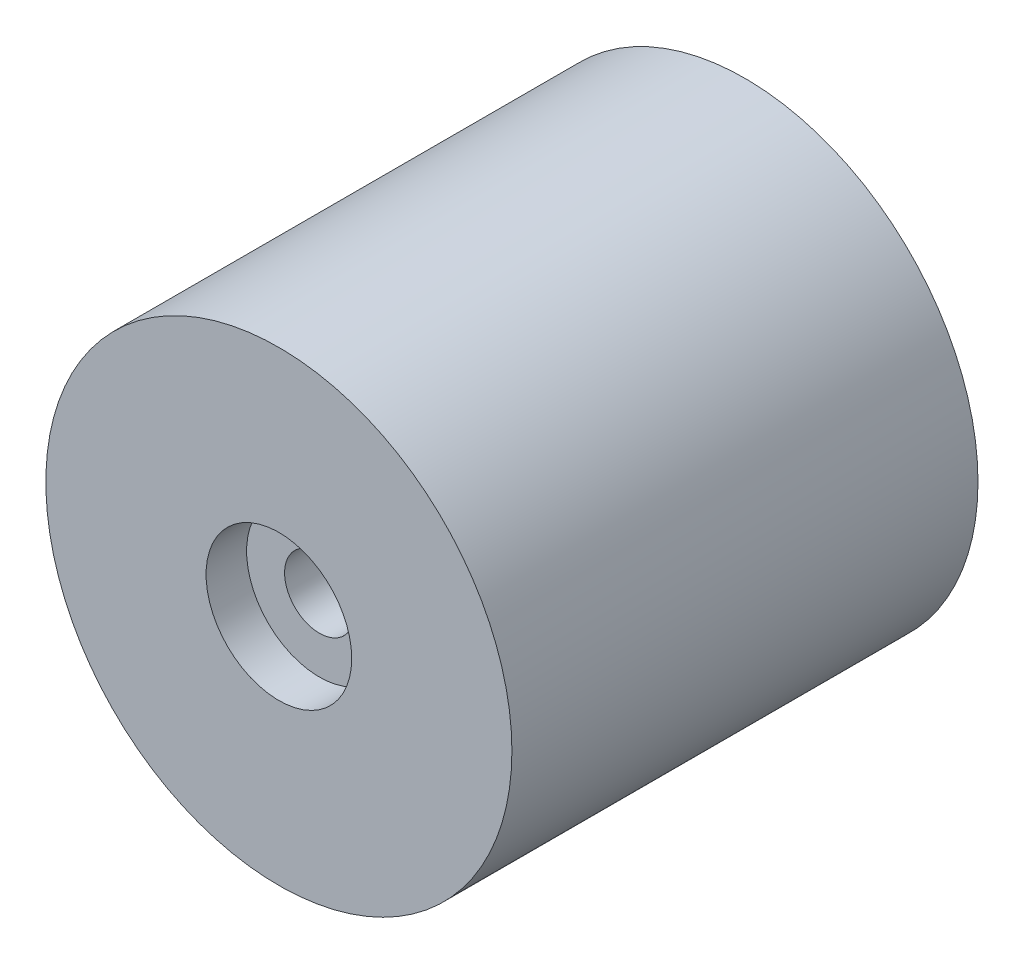
SolidWorks part; units mm, degrees
material "Custom Plastic"
ref_plane "Front Plane" through (0, 0, 0) normal (0, 0, 1) x (1, 0, 0)
ref_plane "Top Plane" through (0, 0, 0) normal (0, 1, 0) x (1, 0, 0)
ref_plane "Right Plane" through (0, 0, 0) normal (1, 0, 0) x (0, 0, -1)
sketch "Sketch1" plane through (0, 0, 0) normal (0, 0, 1) x (1, 0, 0)
  circle A0 centre (0, 0) radius 12.7
  dimension "D1" = 25.4
extrude "Boss-Extrude1" add sketch "Sketch1" against normal blind 25.4
hole_wizard "CBORE for #6 Binding Head Machine Screw1" positions "3DSketch2" profile "Sketch3" counterbore size "#6" standard "ANSI Inch" end condition through all
sketch3d "3DSketch2"
  point P0 (0, 0, 0)
sketch "Sketch3" plane through (0, 0, 0) normal (1, 0, 0) x (0, -1, 0)
  line L0 (0, 0) -> (0, 25.4)
  line L1 (0, 25.4) -> (1.8986, 25.4)
  line L3 (1.8986, 25.4) -> (1.8987, 2.2098)
  line L4 (1.8987, 2.2098) -> (3.9687, 2.2098)
  line L5 (3.9687, 2.2098) -> (3.9687, 0)
  line L7 (3.9687, 0) -> (0, 0)
  line L11 (0, -6.35) -> (0, 107.95) construction
  dimension "Thru Hole Dia." = 3.7973
  dimension "Thru Hole Depth" = 25.4
  dimension "C'Bore Dia." = 7.9375
  dimension "C'Bore Depth" = 2.2098
